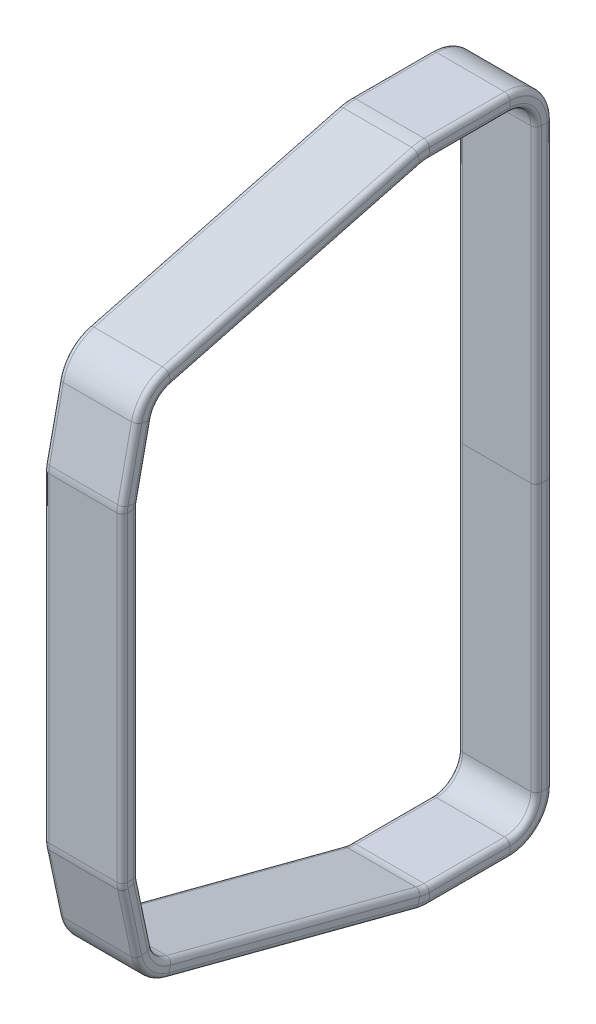
SolidWorks part; units mm, degrees
material "Nylon"
ref_plane "Front Plane" through (0, 0, 0) normal (0, 0, 1) x (1, 0, 0)
ref_plane "Top Plane" through (0, 0, 0) normal (0, 1, 0) x (1, 0, 0)
ref_plane "Right Plane" through (0, 0, 0) normal (1, 0, 0) x (0, 0, -1)
ref_plane "Plane1" through (12.653, 0, 0) normal (1, 0, 0) x (0, 0, -1)
sketch "Sketch2" plane through (12.653, 0, 0) normal (1, 0, 0) x (0, 0, -1)
  line L0 (0.8255, -25.8837) -> (0.8255, 29.9963) construction
  line L1 (0.8255, -25.8837) -> (0.8255, 29.9963)
  line L2 (-9.525, 32.5363) -> (2.032, 32.5363) construction
  line L3 (-9.525, 32.5363) -> (-1.7145, 32.5363)
  line L4 (-34.4892, 26.1034) -> (-10.3296, 32.4327)
  line L5 (0.8255, 2.0563) -> (-40.6949, 2.0563) construction
  line L6 (-37.6654, 17.8861) -> (-36.3301, 24.174)
  line L7 (-37.7, 17.5563) -> (-37.5, 17.5563) construction
  line L8 (-37.7, 17.5563) -> (-35.6382, 17.5563) construction
  line L9 (-37.7, 17.5563) -> (-37.7, -13.4437) construction
  line L10 (-37.7, 17.5563) -> (-37.7, -13.4437)
  line L11 (-9.525, -28.4237) -> (-1.7145, -28.4237)
  line L13 (-34.4892, -21.9907) -> (-10.3296, -28.32)
  line L14 (-37.6654, -13.7734) -> (-36.3301, -20.0613)
  arc A0 (0.8255, 29.9963) -> (-1.7145, 32.5363) centre (-1.7145, 29.9963) ccw construction
  arc A1 (0.8255, 29.9963) -> (-1.7145, 32.5363) centre (-1.7145, 29.9963) ccw
  arc A2 (-9.525, 32.5363) -> (-12.7, 29.3613) centre (-9.525, 29.3613) ccw construction
  arc A3 (-9.525, 32.5363) -> (-10.3296, 32.4327) centre (-9.525, 29.3613) ccw
  arc A4 (-33.8455, 26.1863) -> (-36.3855, 23.6463) centre (-33.8455, 23.6463) ccw construction
  arc A5 (-34.4892, 26.1034) -> (-36.3301, 24.174) centre (-33.8455, 23.6463) ccw
  arc A6 (-37.7, 17.5563) -> (-37.6654, 17.8861) centre (-36.1125, 17.5563) cw
  arc A7 (0.8255, -25.8837) -> (-1.7145, -28.4237) centre (-1.7145, -25.8837) cw
  arc A8 (-9.525, -28.4237) -> (-10.3296, -28.32) centre (-9.525, -25.2487) cw
  arc A9 (-34.4892, -21.9907) -> (-36.3301, -20.0613) centre (-33.8455, -19.5337) cw
  arc A10 (-37.7, -13.4437) -> (-37.6654, -13.7734) centre (-36.1125, -13.4437) ccw
  point P32 (-37.7, 2.0563)
  dimension "D1" = 1.5875
sketch "Sketch3" plane through (0, 0, 0) normal (0, 1, 0) x (1, 0, 0)
  line L1 (16.463, 0.8255) -> (8.843, 0.8255)
  line L2 (16.463, 0.8255) -> (16.463, 2.413)
  line L3 (16.463, 2.413) -> (8.843, 2.413)
  line L4 (8.843, 0.8255) -> (8.843, 2.413)
  point P4 (12.653, 0.8255)
  dimension "D1" = 1.5875
  dimension "D2" = 7.62
sweep "Sweep1" add profiles "Sketch3" path "Sketch2"
fillet "Fillet1" radius 0.508 68 edges at (16.463, -12.9418, -2.413) (8.843, -12.9418, -2.413) (8.843, -12.9418, -0.8255) (16.463, -12.9418, -0.8255) (16.463, -28.8022, -1.2041) (8.843, -28.8022, -1.2041) (8.843, -27.6797, -0.0816) (16.463, -27.6797, -0.0816) (16.463, 30.8037, 22.8117) (8.843, 30.8037, 22.8117) (8.843, 29.2681, 22.4094) (16.463, 29.2681, 22.4094) (16.463, 34.0848, 10.1335) (8.843, 34.0848, 10.1335) (8.843, 32.5103, 9.9306) (16.463, 32.5103, 9.9306) (16.463, 34.1238, 5.6197) (8.843, 34.1238, 5.6197) (8.843, 32.5363, 5.6197) (16.463, 32.5363, 5.6197) (16.463, 32.9149, -1.2041) (8.843, 32.9149, -1.2041) (8.843, 31.7924, -0.0816) (16.463, 31.7924, -0.0816) (16.463, 14.9982, -2.413) (8.843, 14.9982, -2.413) (16.463, 14.9982, -0.8255) (8.843, 14.9982, -0.8255) (16.463, -30.0112, 5.6197) (8.843, -30.0112, 5.6197) (8.843, -28.4237, 5.6197) (16.463, -28.4237, 5.6197) (16.463, -29.9721, 10.1335) (8.843, -29.9721, 10.1335) (8.843, -28.3976, 9.9306) (16.463, -28.3976, 9.9306) (16.463, -26.6911, 22.8117) (8.843, -26.6911, 22.8117) (8.843, -25.1554, 22.4094) (16.463, -25.1554, 22.4094) (16.463, -22.3829, 36.8318) (8.843, -22.3829, 36.8318) (8.843, -21.287, 35.6832) (16.463, -21.287, 35.6832) (16.463, -17.2471, 38.5506) (8.843, -17.2471, 38.5506) (8.843, -16.9174, 36.9977) (16.463, -16.9174, 36.9977) (16.463, -13.7752, 39.2701) (8.843, -13.7752, 39.2701) (8.843, -13.6094, 37.6913) (16.463, -13.6094, 37.6913) (16.463, 2.0563, 39.2875) (8.843, 2.0563, 39.2875) (8.843, 2.0563, 37.7) (16.463, 2.0563, 37.7) (16.463, 17.8879, 39.2701) (8.843, 17.8879, 39.2701) (8.843, 17.7221, 37.6913) (16.463, 17.7221, 37.6913) (16.463, 21.3598, 38.5506) (8.843, 21.3598, 38.5506) (8.843, 21.03, 36.9977) (16.463, 21.03, 36.9977) (16.463, 26.4956, 36.8318) (8.843, 26.4956, 36.8318) (8.843, 25.3997, 35.6832) (16.463, 25.3997, 35.6832)
